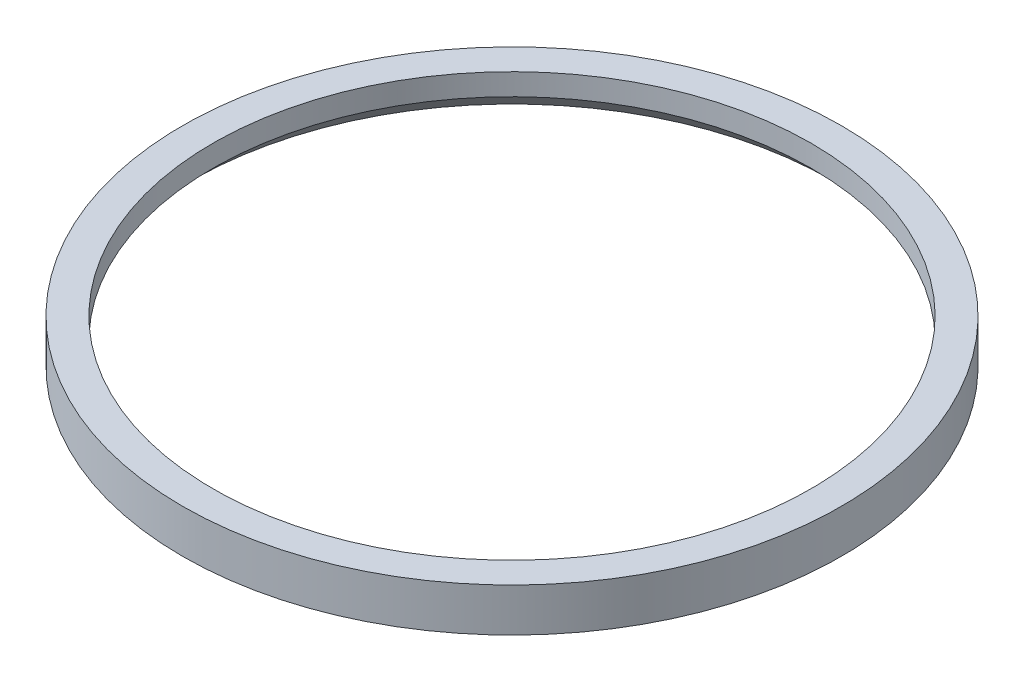
SolidWorks part; units mm, degrees
ref_plane "Front Plane" through (0, 0, 0) normal (0, 0, 1) x (1, 0, 0)
ref_plane "Top Plane" through (0, 0, 0) normal (0, 1, 0) x (1, 0, 0)
ref_plane "Right Plane" through (0, 0, 0) normal (1, 0, 0) x (0, 0, -1)
sketch "Sketch1" plane through (0, 0, 0) normal (0, 0, 1) x (1, 0, 0)
  line L0 (19, 0) -> (0, 0) construction
  line L1 (0, 0) -> (0, 45.5789) construction
  line L2 (19, 0) -> (19, 2.5)
  line L3 (19, 2.5) -> (17.25, 2.5)
  line L4 (17.25, 2.5) -> (17.25, 1.25)
  line L5 (17.25, 1.25) -> (18.5, 0)
  line L6 (18.5, 0) -> (19, 0)
  dimension "D1" = 45
  dimension "D2" = 1.25
  dimension "D3" = 2.5
  dimension "D4" = 1.75
  dimension "D5" = 19
revolve "Revolve1" add sketch "Sketch1" angle 360 about L1
